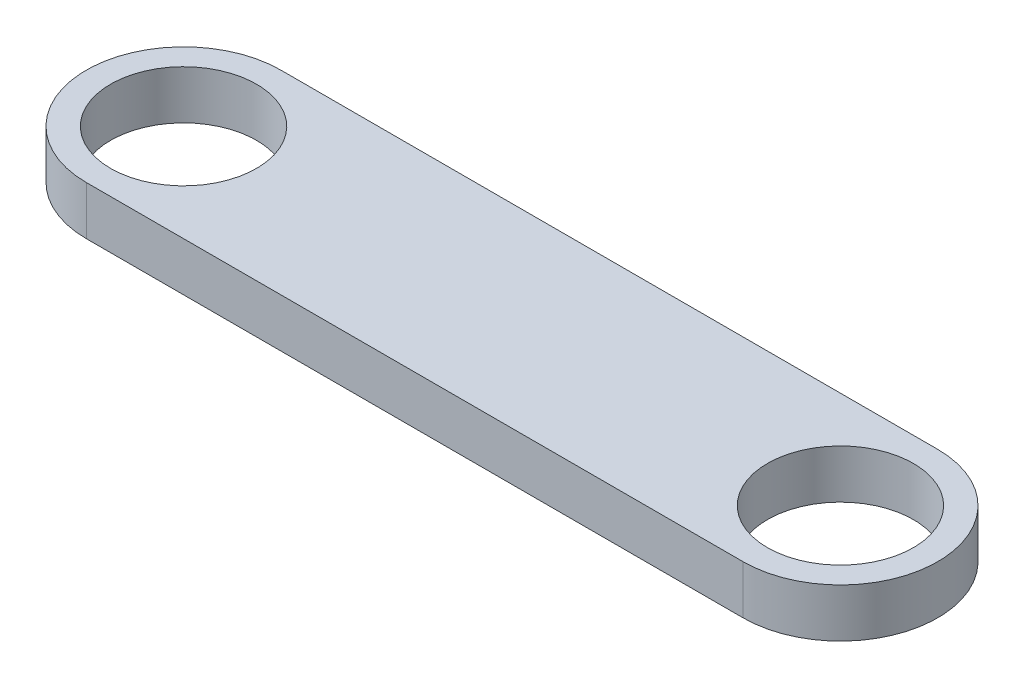
SolidWorks part; units mm, degrees
ref_plane "Front Plane" through (0, 0, 0) normal (0, 0, 1) x (1, 0, 0)
ref_plane "Top Plane" through (0, 0, 0) normal (0, 1, 0) x (1, 0, 0)
ref_plane "Right Plane" through (0, 0, 0) normal (1, 0, 0) x (0, 0, -1)
sketch "Sketch1" plane through (0, 0, 0) normal (0, 1, 0) x (1, 0, 0)
  line L0 (-134.1867, 0) -> (0.8133, 0) construction
  line L1 (-134.1867, 20) -> (0.8133, 20)
  line L2 (-134.1867, -20) -> (0.8133, -20)
  arc A0 (-134.1867, 20) -> (-134.1867, -20) centre (-134.1867, 0) ccw
  arc A1 (0.8133, -20) -> (0.8133, 20) centre (0.8133, 0) ccw
  circle A2 centre (-134.1867, 0) radius 15
  point P3 (-66.6867, 0)
  dimension "D1" = 40
  dimension "D2" = 135
extrude "Boss-Extrude1" add sketch "Sketch1" along normal blind 10
sketch "Sketch2" plane through (0, 10, 0) normal (0, 1, 0) x (1, 0, 0)
  circle A0 centre (0.8133, 0) radius 15
extrude "Cut-Extrude1" cut sketch "Sketch2" against normal blind 10
